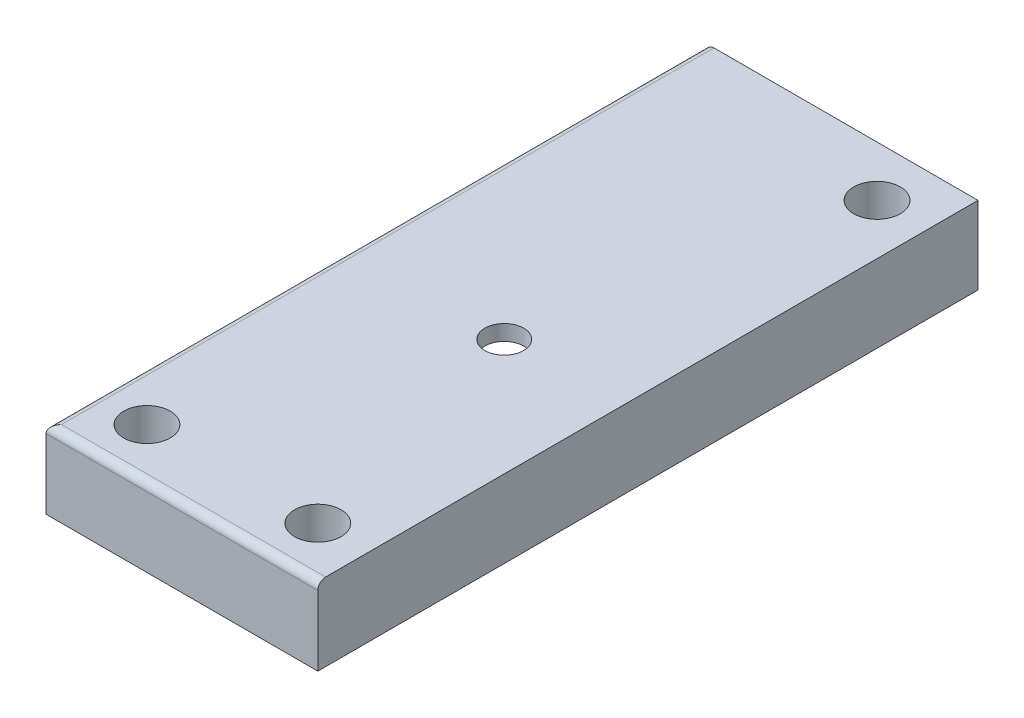
SolidWorks part; units mm, degrees
ref_plane "Front Plane" through (0, 0, 0) normal (0, 0, 1) x (1, 0, 0)
ref_plane "Top Plane" through (0, 0, 0) normal (0, 1, 0) x (1, 0, 0)
ref_plane "Right Plane" through (0, 0, 0) normal (1, 0, 0) x (0, 0, -1)
sketch "Sketch1" plane through (0, 0, 0) normal (0, 1, 0) x (1, 0, 0)
  line L1 (-17.5, 42.5) -> (17.5, 42.5)
  line L2 (-17.5, 42.5) -> (-17.5, -42.5)
  line L3 (-17.5, -42.5) -> (17.5, -42.5)
  line L4 (17.5, 42.5) -> (17.5, -42.5)
  line L5 (-17.5, 42.5) -> (17.5, -42.5) construction
  line L6 (-17.5, -42.5) -> (17.5, 42.5) construction
  point P0 (0, 0)
  dimension "D1" = 85
  dimension "D2" = 35
extrude "Boss-Extrude1" add sketch "Sketch1" along normal blind 10
sketch "Sketch2" plane through (0, 0, 0) normal (0, -1, 0) x (1, 0, 0)
  line L1 (-15.5, 40.5) -> (15.5, 40.5)
  line L2 (-15.5, 40.5) -> (-15.5, -40.5)
  line L3 (-15.5, -40.5) -> (15.5, -40.5)
  line L4 (15.5, 40.5) -> (15.5, -40.5)
  line L5 (-15.5, 40.5) -> (15.5, -40.5) construction
  line L6 (-15.5, -40.5) -> (15.5, 40.5) construction
  point P0 (0, 0)
  dimension "D1" = 31
  dimension "D2" = 81
extrude "Cut-Extrude1" cut sketch "Sketch2" against normal blind 8
sketch "Sketch3" plane through (0, 8, 0) normal (0, -1, 0) x (1, 0, 0)
  line L1 (-15.5, 40.5) -> (-6.5, 40.5)
  line L2 (-15.5, 40.5) -> (-15.5, 31.5)
  line L3 (-15.5, 31.5) -> (-6.5, 31.5)
  line L4 (-6.5, 40.5) -> (-6.5, 31.5)
  line L5 (15.5, 40.5) -> (6.5, 40.5)
  line L6 (15.5, 40.5) -> (15.5, 31.5)
  line L7 (15.5, 31.5) -> (6.5, 31.5)
  line L8 (6.5, 40.5) -> (6.5, 31.5)
  line L9 (15.5, -40.5) -> (6.5, -40.5)
  line L10 (15.5, -40.5) -> (15.5, -31.5)
  line L11 (15.5, -31.5) -> (6.5, -31.5)
  line L12 (6.5, -40.5) -> (6.5, -31.5)
  circle A0 centre (-11, 36) radius 1.25
  circle A1 centre (11, 36) radius 1.25
  circle A2 centre (11, -36) radius 1.25
  dimension "D7" = 4.5
  dimension "D8" = 4.5
  dimension "D9" = 4.5
  dimension "D10" = 4.5
  dimension "D11" = 4.5
  dimension "D12" = 4.5
  dimension "D13" = 2.5
  dimension "D14" = 2.5
  dimension "D15" = 2.5
  dimension "D1" = 9
  dimension "D2" = 9
  dimension "D3" = 9
  dimension "D4" = 9
  dimension "D5" = 9
  dimension "D6" = 9
extrude "Boss-Extrude2" add sketch "Sketch3" along normal blind 8
sketch "Sketch4" plane through (0, 0, 0) normal (0, -1, 0) x (1, 0, 0)
  circle A0 centre (-11, 36) radius 1.25
  circle A1 centre (11, 36) radius 1.25
  circle A2 centre (11, -36) radius 1.25
extrude "Cut-Extrude3" cut sketch "Sketch4" against normal blind 10
sketch "Sketch5" plane through (0, 10, 0) normal (0, 1, 0) x (1, 0, 0)
  circle A0 centre (11, -36) radius 3
  circle A1 centre (-11, -36) radius 3
  circle A2 centre (11, 36) radius 3
  dimension "D1" = 6
  dimension "D2" = 6
  dimension "D3" = 6
extrude "Cut-Extrude4" cut sketch "Sketch5" against normal blind 5
fillet "Fillet1" radius 1 2 edges at (-17.5, 10, 0) (0, 10, 42.5)
sketch "Sketch6" plane through (0, 10, 0) normal (0, 1, 0) x (1, 0, 0)
  line L0 (-17.5, -42.5) -> (-17.5, 42.5) construction
  line L1 (17.5, -42.5) -> (-17.5, -42.5) construction
  circle A0 centre (2.5, -3.5) radius 2.5
  dimension "D1" = 20
  dimension "D2" = 39
  dimension "D3" = 5
extrude "Cut-Extrude5" cut sketch "Sketch6" against normal blind 5
